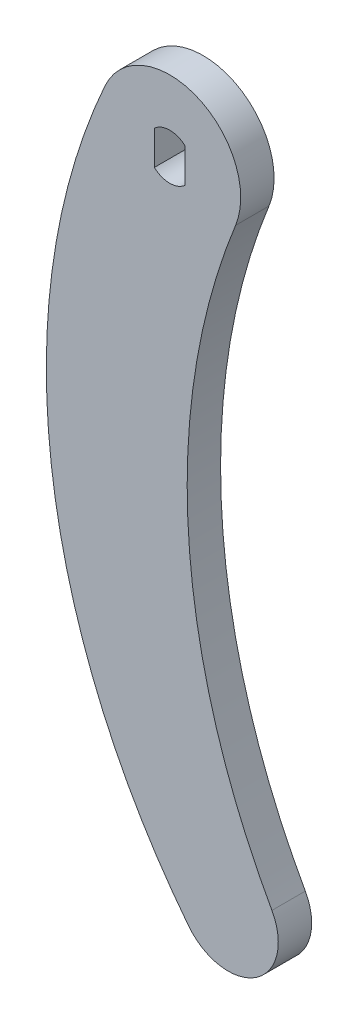
SolidWorks part; units mm, degrees
material "PLA"
ref_plane "Front Plane" through (0, 0, 0) normal (0, 0, 1) x (1, 0, 0)
ref_plane "Top Plane" through (0, 0, 0) normal (0, 1, 0) x (1, 0, 0)
ref_plane "Right Plane" through (0, 0, 0) normal (1, 0, 0) x (0, 0, -1)
sketch "Sketch1" plane through (0, 0, 0) normal (0, 0, 1) x (1, 0, 0)
  line L2 (-1.85, -2.04) -> (-1.85, 2.04)
  line L4 (1.85, -2.04) -> (1.85, 2.04)
  line L5 (-1.85, -2.04) -> (1.85, 2.04) construction
  line L6 (-1.85, 2.04) -> (1.85, -2.04) construction
  arc A0 (7.8841, -3.1765) -> (-7.7527, 3.485) centre (0, 0) ccw
  arc A1 (2.2799, -78.7042) -> (12.2387, -72.0749) centre (7, -75) ccw
  arc A2 (-7.7527, 3.485) -> (2.2799, -78.7042) centre (65.2141, -29.315) ccw
  arc A3 (7.8841, -3.1765) -> (12.2387, -72.0749) centre (82.0877, -33.0735) ccw
  arc A4 (-1.85, -2.04) -> (1.85, -2.04) centre (0, 0) ccw
  arc A5 (1.85, 2.04) -> (-1.85, 2.04) centre (0, 0) ccw
  dimension "D1" = 3.7
  dimension "D3" = 17
  dimension "D4" = 6
  dimension "D7" = 80
  dimension "D8" = 80
  dimension "D2" = 4.08
  dimension "D5" = 7
  dimension "D6" = 75
extrude "Boss-Extrude1" add sketch "Sketch1" along normal blind 4
